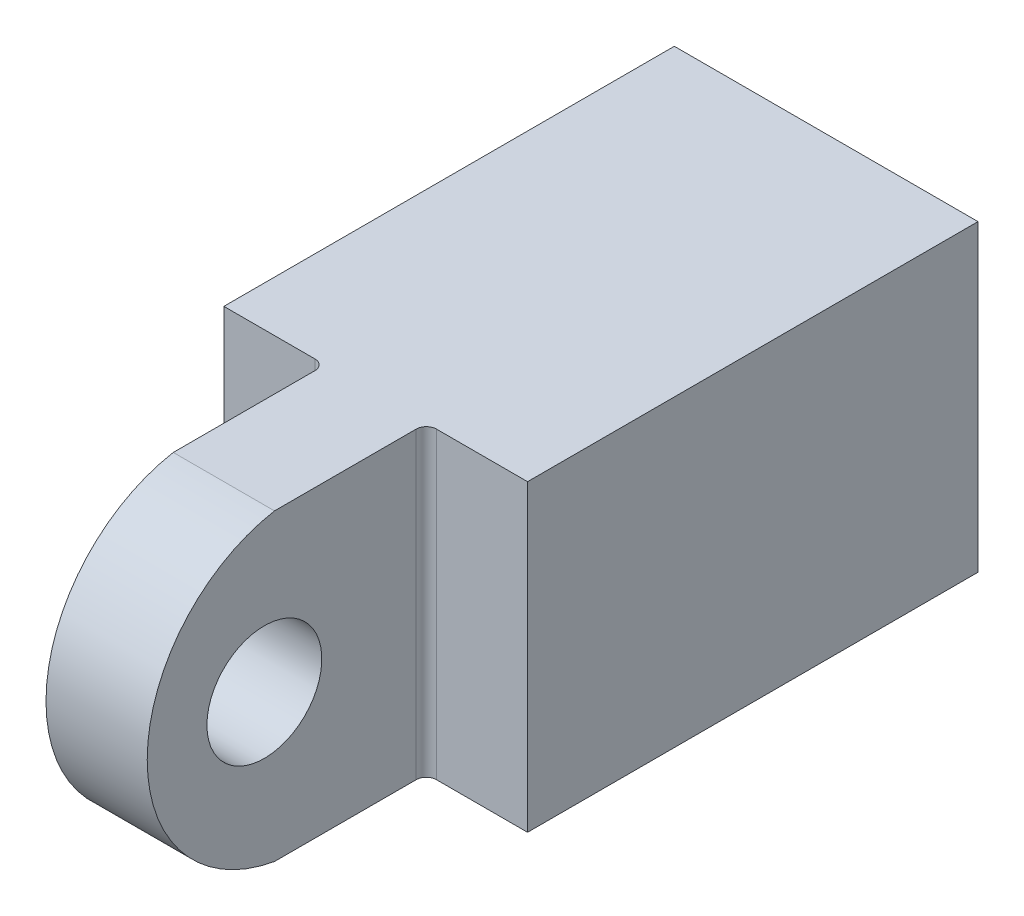
SolidWorks part; units mm, degrees
ref_plane "Front Plane" through (0, 0, 0) normal (0, 0, 1) x (1, 0, 0)
ref_plane "Top Plane" through (0, 0, 0) normal (0, 1, 0) x (1, 0, 0)
ref_plane "Right Plane" through (0, 0, 0) normal (1, 0, 0) x (0, 0, -1)
sketch "Sketch2" plane through (0, 0, 0) normal (0, 0, 1) x (1, 0, 0)
  line L1 (-30, 30) -> (30, 30)
  line L2 (-30, 30) -> (-30, -30)
  line L3 (-30, -30) -> (30, -30)
  line L4 (30, 30) -> (30, -30)
  line L5 (-30, 30) -> (30, -30) construction
  line L6 (-30, -30) -> (30, 30) construction
  point P0 (0, 0)
  dimension "D1" = 60
  dimension "D2" = 60
extrude "Boss-Extrude1" add sketch "Sketch2" along normal blind 89
ref_plane "Plane1" through (0, 0, 89) normal (0, 0, 1) x (1, 0, 0)
sketch "Sketch3" plane through (0, 0, 89) normal (0, 0, 1) x (1, 0, 0)
  line L0 (30, 30) -> (-30, 30) construction
  line L1 (10, -30) -> (-10, -30)
  line L2 (10, -30) -> (10, 30)
  line L3 (10, 30) -> (-10, 30)
  line L4 (-10, -30) -> (-10, 30)
  line L5 (10, -30) -> (-10, 30) construction
  line L6 (10, 30) -> (-10, -30) construction
  point P0 (0, 0)
  dimension "D1" = 20
extrude "Boss-Extrude2" add sketch "Sketch3" along normal blind 30
ref_plane "Plane2" through (10, 0, 0) normal (1, 0, 0) x (0, 0, -1)
sketch "Sketch4" plane through (10, 0, 0) normal (1, 0, 0) x (0, 0, -1)
  line L0 (-119, -30) -> (-119, 30)
  arc A0 (-119, -30) -> (-119, 30) centre (-113.6759, 0) cw
extrude "Boss-Extrude3" add sketch "Sketch4" against normal blind 20
fillet "Fillet1" radius 2 2 edges at (10, 0, 89) (-10, 0, 89)
ref_plane "Plane4" through (0, 0, 0) normal (0, 0, -1) x (-1, 0, 0)
sketch "Sketch7" plane through (0, 0, 0) normal (0, 0, -1) x (-1, 0, 0)
  line L0 (30, 30) -> (30, -30) construction
  line L1 (-25, 25) -> (25, 25)
  line L2 (-25, 25) -> (-25, -25)
  line L3 (-25, -25) -> (25, -25)
  line L4 (25, 25) -> (25, -25)
  line L5 (-25, 25) -> (25, -25) construction
  line L6 (-25, -25) -> (25, 25) construction
  line L7 (-30, 30) -> (30, 30) construction
  point P0 (0, 0)
  dimension "D1" = 5
  dimension "D2" = 5
extrude "Cut-Extrude1" cut sketch "Sketch7" against normal blind 81 contours L4 L3 L2 L1
ref_plane "Plane5" through (-10, 0, 0) normal (-1, 0, 0) x (0, 0, 1)
sketch "Sketch8" plane through (-10, 0, 0) normal (-1, 0, 0) x (0, 0, 1)
  line L0 (91, 30) -> (91, -30) construction
  circle A0 centre (121, 0) radius 11.35
  dimension "D1" = 22.7
  dimension "D2" = 30
extrude "Cut-Extrude2" cut sketch "Sketch8" against normal through all
